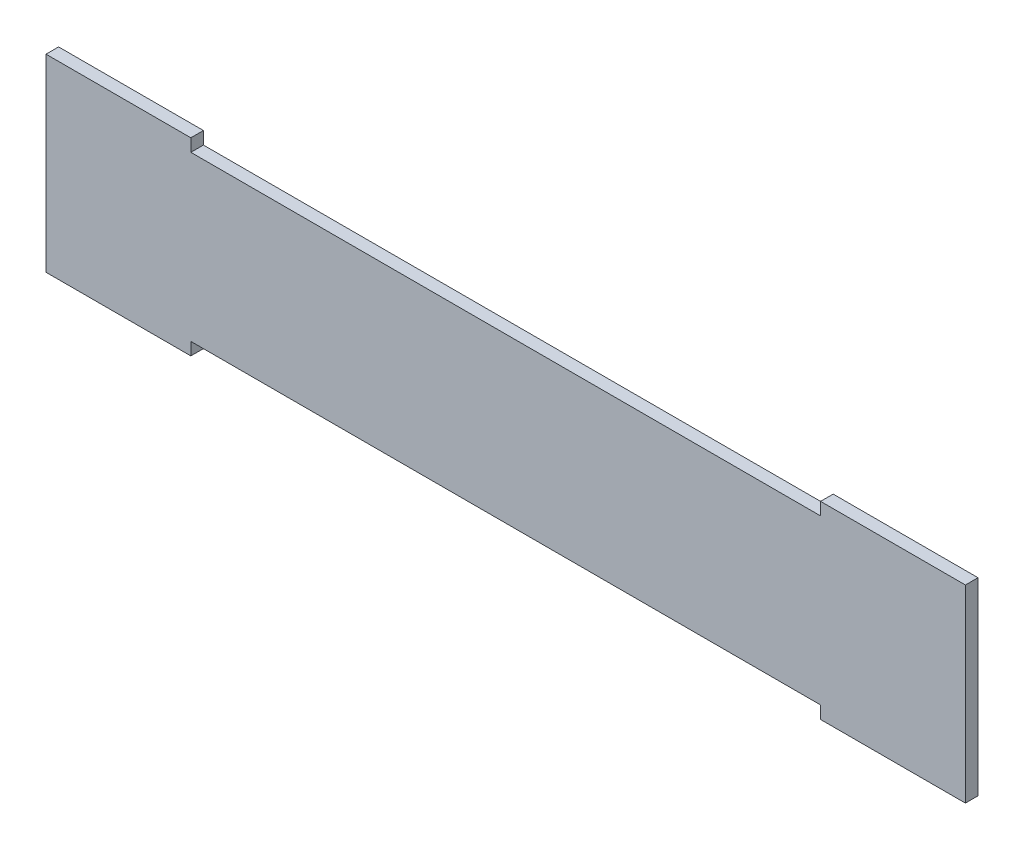
SolidWorks part; units mm, degrees
ref_plane "Front Plane" through (0, 0, 0) normal (0, 0, 1) x (1, 0, 0)
ref_plane "Top Plane" through (0, 0, 0) normal (0, 1, 0) x (1, 0, 0)
ref_plane "Right Plane" through (0, 0, 0) normal (1, 0, 0) x (0, 0, -1)
sketch "Sketch1" plane through (0, 0, 0) normal (0, 0, 1) x (1, 0, 0)
  line L0 (0, 0) -> (0, -15)
  line L1 (0, -15) -> (23, -15)
  line L2 (23, -15) -> (23, -13)
  line L3 (23, -13) -> (123, -13)
  line L4 (123, -13) -> (123, -15)
  line L5 (123, -15) -> (146, -15)
  line L6 (146, -15) -> (146, 0)
  line L7 (0, 0) -> (146, 0)
  dimension "D1" = 100
  dimension "D2" = 23
  dimension "D3" = 23
  dimension "D4" = 15
  dimension "D6" = 2
  dimension "D7" = 2
extrude "Boss-Extrude1" add sketch "Sketch1" along normal blind 2
mirror "Mirror3" about plane through (0, 0, 2) normal (0, -1, 0) of "Boss-Extrude1"
